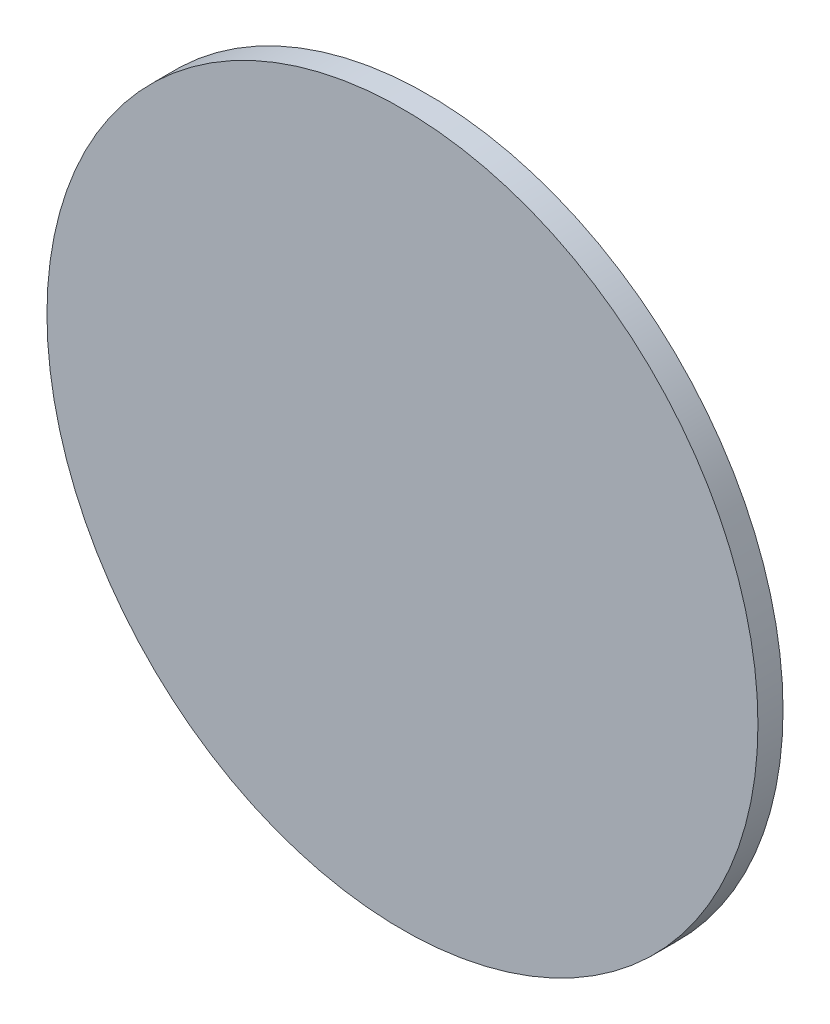
SolidWorks part; units mm, degrees
ref_plane "前视基准面" through (0, 0, 0) normal (0, 0, 1) x (1, 0, 0)
ref_plane "上视基准面" through (0, 0, 0) normal (0, 1, 0) x (1, 0, 0)
ref_plane "右视基准面" through (0, 0, 0) normal (1, 0, 0) x (0, 0, -1)
other "Configuration Table"
sketch "草图1" plane through (0, 0, 0) normal (0, 0, 1) x (1, 0, 0)
  circle A0 centre (0, 0) radius 42.5
  dimension "D1" = 85
extrude "凸台-拉伸1" add sketch "草图1" along normal blind 3
